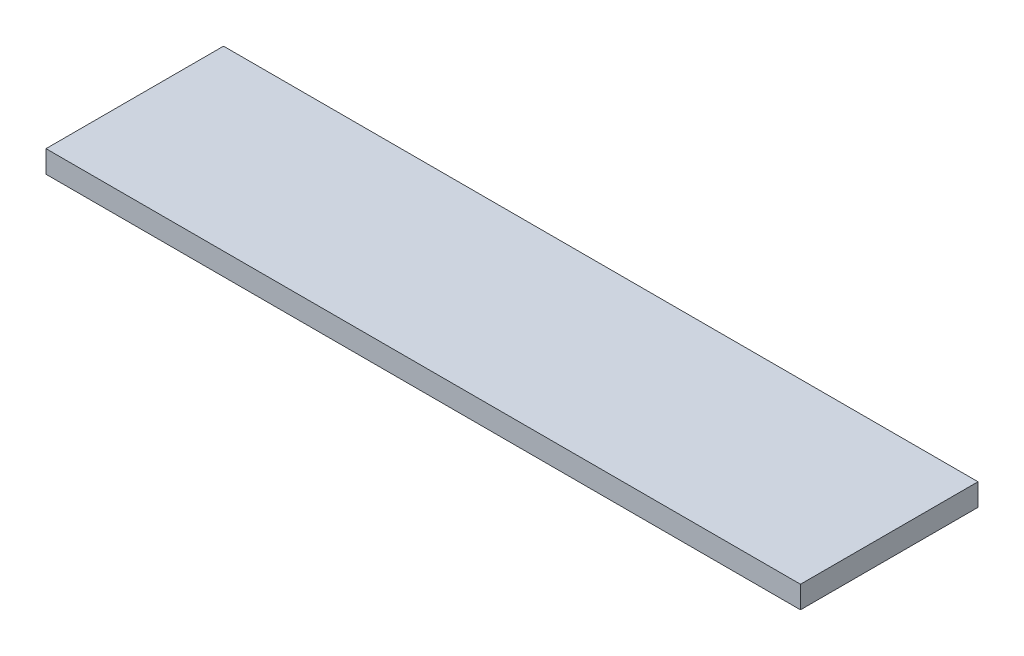
SolidWorks part; units mm, degrees
ref_plane "Front Plane" through (0, 0, 0) normal (0, 0, 1) x (1, 0, 0)
ref_plane "Top Plane" through (0, 0, 0) normal (0, 1, 0) x (1, 0, 0)
ref_plane "Right Plane" through (0, 0, 0) normal (1, 0, 0) x (0, 0, -1)
sketch "Sketch1" plane through (0, 0, 0) normal (0, 1, 0) x (1, 0, 0)
  line L1 (-85, 20) -> (85, 20)
  line L2 (-85, 20) -> (-85, -20)
  line L3 (-85, -20) -> (85, -20)
  line L4 (85, 20) -> (85, -20)
  line L5 (-85, 20) -> (85, -20) construction
  line L6 (-85, -20) -> (85, 20) construction
  point P0 (0, 0)
  dimension "D1" = 170
  dimension "D2" = 40
extrude "Boss-Extrude1" add sketch "Sketch1" along normal blind 5
